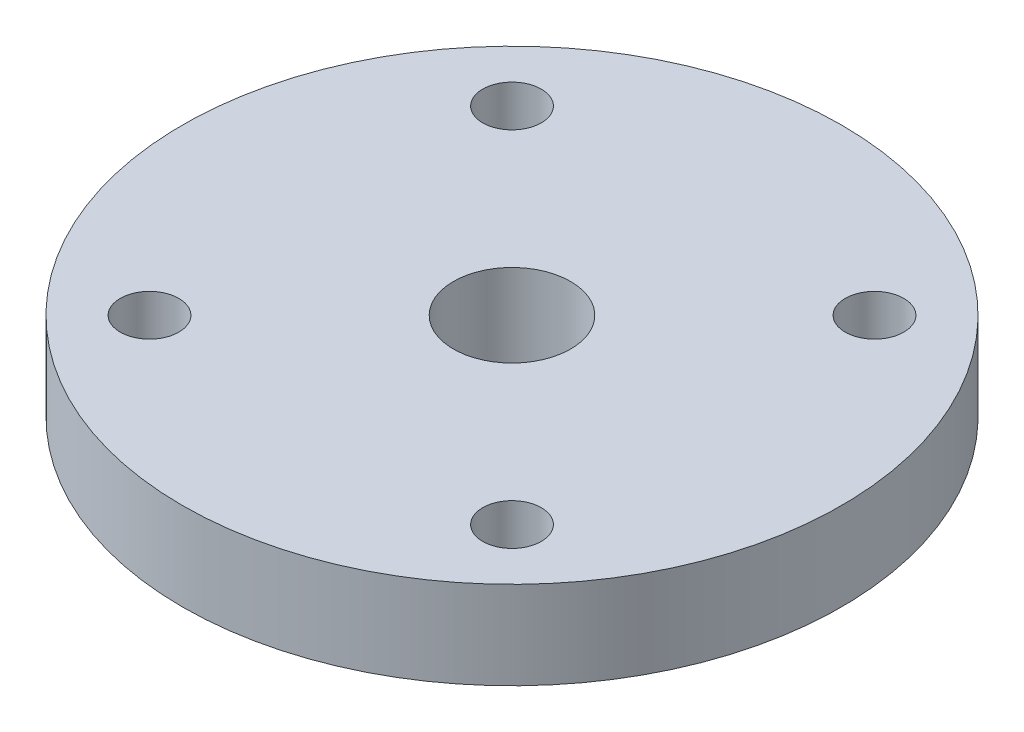
SolidWorks part; units mm, degrees
ref_plane "Front Plane" through (0, 0, 0) normal (0, 0, 1) x (1, 0, 0)
ref_plane "Top Plane" through (0, 0, 0) normal (0, 1, 0) x (1, 0, 0)
ref_plane "Right Plane" through (0, 0, 0) normal (1, 0, 0) x (0, 0, -1)
sketch "Sketch1" plane through (0, 0, 0) normal (0, 1, 0) x (1, 0, 0)
  line L2 (11.5, -4.899) -> (11.5, 4.899)
  line L4 (-11.5, -4.899) -> (-11.5, 4.899)
  line L5 (10.4935, -6.7924) -> (-10.4935, 6.7924) construction
  line L6 (10.4935, 6.7924) -> (-10.4935, -6.7924) construction
  arc A0 (11.5, 4.899) -> (-11.5, 4.899) centre (0, 0) ccw
  arc A1 (-11.5, -4.899) -> (11.5, -4.899) centre (0, 0) ccw
  point P4 (-11.5, 0)
  dimension "D1" = 25
  dimension "D2" = 23
  dimension "D3" = 9.798
extrude "bit attached to shaft" add sketch "Sketch1" along normal blind 2
sketch "Sketch2" plane through (0, 2, 0) normal (0, 1, 0) x (1, 0, 0)
  circle A0 centre (0, 0) radius 22.5
  dimension "D1" = 45
extrude "Boss-Extrude2" add sketch "Sketch2" along normal blind 6
sketch "Sketch3" plane through (0, 2, 0) normal (0, -1, 0) x (1, 0, 0)
  line L1 (0, 0) -> (22.5, 0) construction
  circle A0 centre (0, 0) radius 17.5 construction
  circle A2 centre (12.3744, -12.3744) radius 2
  circle A3 centre (12.3744, -12.3744) radius 2
  circle A4 centre (12.3744, 12.3744) radius 2
  circle A5 centre (-12.3744, -12.3744) radius 2
  circle A6 centre (-12.3744, 12.3744) radius 2
  point P12 (0, 0)
  point P15 (0, 0)
  point P21 (0, 0)
  dimension "D1" = 35
  dimension "D2" = 4
extrude "Cut-Extrude1" cut sketch "Sketch3" against normal blind 6 contours A5 | A2 | A4 | A6
sketch "Sketch4" plane through (0, 0, 0) normal (0, -1, 0) x (1, 0, 0)
  circle A0 centre (0, 0) radius 4
  dimension "D1" = 8
extrude "Cut-Extrude2" cut sketch "Sketch4" against normal through all
